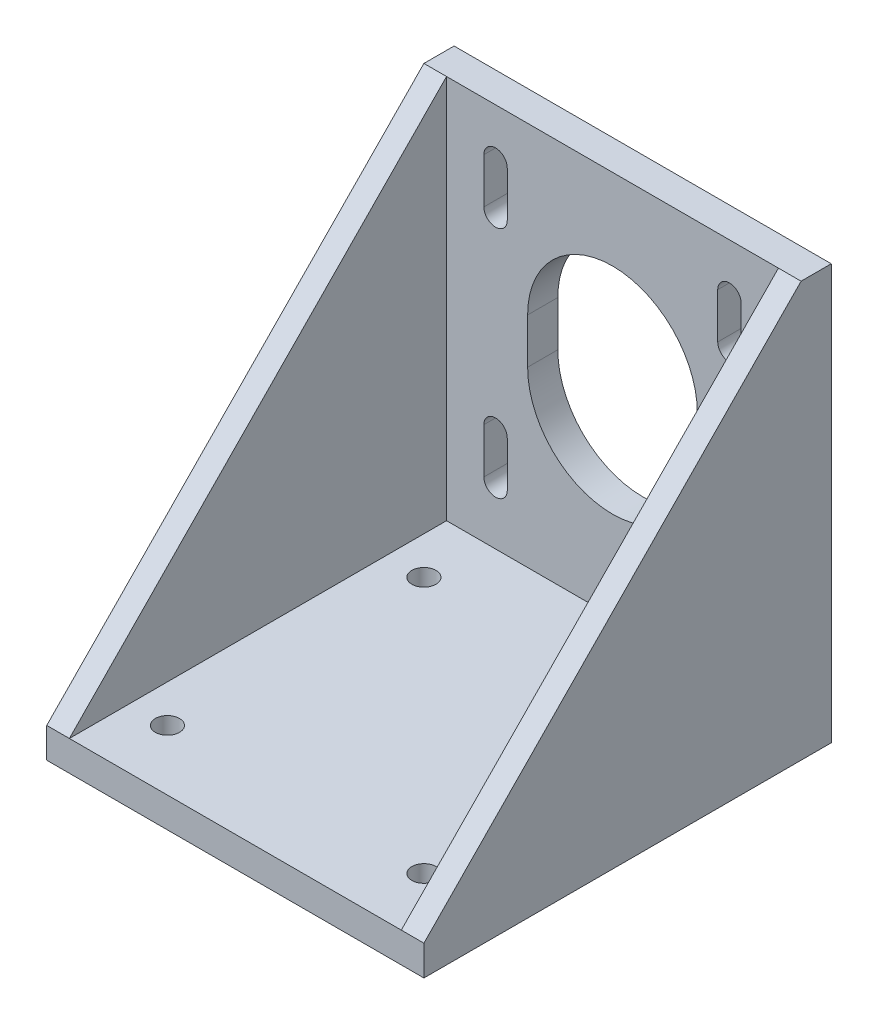
SolidWorks part; units mm, degrees
ref_plane "Front Plane" through (0, 0, 0) normal (0, 0, 1) x (1, 0, 0)
ref_plane "Top Plane" through (0, 0, 0) normal (0, 1, 0) x (1, 0, 0)
ref_plane "Right Plane" through (0, 0, 0) normal (1, 0, 0) x (0, 0, -1)
sketch "Sketch2" plane through (0, 0, 0) normal (0, 1, 0) x (1, 0, 0)
  line L0 (35.55, 81.6781) -> (25.55, 81.6781)
  line L1 (18.55, 74.6781) -> (18.55, 73.55)
  line L2 (15.55, 70.55) -> (-2.45, 70.55)
  line L3 (-9.45, 63.55) -> (-9.45, -2.45)
  line L4 (-2.45, -9.45) -> (63.55, -9.45)
  line L5 (70.55, -2.45) -> (70.55, 63.55)
  line L6 (63.55, 70.55) -> (45.55, 70.55)
  line L7 (42.55, 73.55) -> (42.55, 74.6781)
  circle A0 centre (30.55, 47.55) radius 1.6
  circle A1 centre (47.55, 47.55) radius 2.55
  circle A2 centre (47.55, 30.55) radius 1.6
  circle A3 centre (47.55, 13.55) radius 2.55
  circle A4 centre (30.55, 13.55) radius 1.6
  circle A5 centre (13.55, 13.55) radius 2.55
  circle A6 centre (13.55, 30.55) radius 1.6
  circle A7 centre (13.55, 47.55) radius 2.55
  circle A8 centre (0, 0) radius 2.7
  circle A9 centre (61.1, 0) radius 2.7
  circle A10 centre (61.1, 61.1) radius 2.7
  circle A11 centre (0, 61.1) radius 2.7
  arc A12 (25.55, 81.6781) -> (18.55, 74.6781) centre (25.55, 74.6781) ccw
  arc A13 (15.55, 70.55) -> (18.55, 73.55) centre (15.55, 73.55) ccw
  arc A14 (-2.45, 70.55) -> (-9.45, 63.55) centre (-2.45, 63.55) ccw
  arc A15 (-9.45, -2.45) -> (-2.45, -9.45) centre (-2.45, -2.45) ccw
  arc A16 (63.55, -9.45) -> (70.55, -2.45) centre (63.55, -2.45) ccw
  arc A17 (70.55, 63.55) -> (63.55, 70.55) centre (63.55, 63.55) ccw
  arc A18 (42.55, 73.55) -> (45.55, 70.55) centre (45.55, 73.55) ccw
  arc A19 (42.55, 74.6781) -> (35.55, 81.6781) centre (35.55, 74.6781) ccw
sketch "Sketch3" plane through (0, 0, 0) normal (0, 1, 0) x (1, 0, 0)
  line L0 (5.55, 55.55) -> (5.55, 5.55)
  line L5 (5.55, 5.55) -> (55.55, 5.55)
  line L6 (55.55, 55.55) -> (55.55, 5.55)
  line L7 (5.55, 55.55) -> (55.55, 55.55)
  circle A0 centre (13.55, 47.55) radius 1.6
  circle A1 centre (47.55, 47.55) radius 1.6
  circle A2 centre (13.55, 13.55) radius 1.6
  circle A3 centre (47.55, 13.55) radius 1.6
extrude "Boss-Extrude1" add sketch "Sketch3" along normal blind 4
sketch "Sketch4" plane through (0, 0, -55.55) normal (0, 0, -1) x (-1, 0, 0)
  line L0 (-30.55, 0) -> (-30.55, 27)
  line L1 (-28.95, 0) -> (-32.15, 0) construction
  line L2 (-52.05, 5.5) -> (-9.05, 5.5)
  line L3 (-9.05, 5.5) -> (-9.05, 48.5)
  line L4 (-9.05, 48.5) -> (-52.05, 48.5)
  line L5 (-52.05, 48.5) -> (-52.05, 5.5)
  circle A0 centre (-46.05, 42.5) radius 1.55
  circle A1 centre (-15.05, 42.5) radius 1.55
  circle A2 centre (-46.05, 11.5) radius 1.55
  circle A3 centre (-30.55, 27) radius 11.25
  circle A4 centre (-15.05, 11.5) radius 1.55
sketch "Sketch5" plane through (0, 0, -55.55) normal (0, 0, -1) x (-1, 0, 0)
  line L2 (-55.55, 4) -> (-55.55, 48.5)
  line L4 (-5.55, 5) -> (-5.55, 48.5)
  line L5 (-46.05, 55) -> (-55.55, 55)
  line L7 (-41.8, 33) -> (-41.8, 27)
  line L9 (-19.3, 33) -> (-19.3, 27)
  line L10 (-55.55, 55) -> (-55.55, 48.5)
  line L11 (-46.05, 55) -> (-5.55, 55)
  line L12 (-5.55, 55) -> (-5.55, 48.5)
  line L13 (-46.05, 48.5) -> (-44.5, 48.5)
  line L14 (-47.6, 48.5) -> (-47.6, 42.5)
  line L16 (-44.5, 48.5) -> (-44.5, 42.5)
  line L17 (-15.05, 48.5) -> (-13.5, 48.5)
  line L18 (-16.6, 48.5) -> (-16.6, 42.5)
  line L20 (-13.5, 48.5) -> (-13.5, 42.5)
  line L22 (-16.6, 17.5) -> (-16.6, 11.5)
  line L24 (-13.5, 17.5) -> (-13.5, 11.5)
  line L26 (-47.6, 17.5) -> (-47.6, 11.5)
  line L28 (-44.5, 17.5) -> (-44.5, 11.5)
  line L30 (-55.55, 4) -> (-55.55, 0)
  line L31 (-55.55, 0) -> (-5.55, 0)
  line L32 (-5.55, 5) -> (-5.55, 0)
  arc A0 (-41.8, 27) -> (-19.3, 27) centre (-30.55, 27) ccw
  arc A1 (-19.3, 33) -> (-41.8, 33) centre (-30.55, 33) ccw
  arc A2 (-44.5, 17.5) -> (-47.6, 17.5) centre (-46.05, 17.5) ccw
  arc A3 (-13.5, 17.5) -> (-16.6, 17.5) centre (-15.05, 17.5) ccw
  arc A4 (-44.5, 48.5) -> (-47.6, 48.5) centre (-46.05, 48.5) ccw
  arc A5 (-13.5, 48.5) -> (-16.6, 48.5) centre (-15.05, 48.5) ccw
  arc A6 (-47.6, 11.5) -> (-44.5, 11.5) centre (-46.05, 11.5) ccw
  arc A7 (-16.6, 11.5) -> (-13.5, 11.5) centre (-15.05, 11.5) ccw
  arc A8 (-16.6, 42.5) -> (-13.5, 42.5) centre (-15.05, 42.5) ccw
  arc A9 (-47.6, 42.5) -> (-44.5, 42.5) centre (-46.05, 42.5) ccw
  line M15 (-55.55, 0) -> (-5.55, 0)
  line M16 (-5.55, 0) -> (-5.55, 4)
  line M17 (-5.55, 4) -> (-55.55, 4)
  line M18 (-55.55, 4) -> (-55.55, 0)
extrude "Boss-Extrude3" add sketch "Sketch5" along normal blind 4 contours M18 M15 M16 M17 | L12 L11 L5 L10 L2 L4 A9 L14 A4 L16 A8 L18 A5 L20 A7 L22 A3 L24 A6 L26 A2 L28 A1 L9 A0 L7 M17
sketch "Sketch7" plane through (55.55, 0, 0) normal (1, 0, 0) x (0, 0, -1)
  line L0 (55.55, 55) -> (5.55, 4)
  line L1 (5.55, 4) -> (55.55, 4)
  line L2 (55.55, 4) -> (55.55, 55)
extrude "Boss-Extrude4" add sketch "Sketch7" against normal blind 3
sketch "Sketch8" plane through (5.55, 0, 0) normal (-1, 0, 0) x (0, 0, 1)
  line L0 (-55.55, 55) -> (-5.55, 4)
  line L1 (-5.55, 4) -> (-55.55, 4)
  line L2 (-55.55, 4) -> (-55.55, 55)
extrude "Boss-Extrude5" add sketch "Sketch8" against normal blind 3
